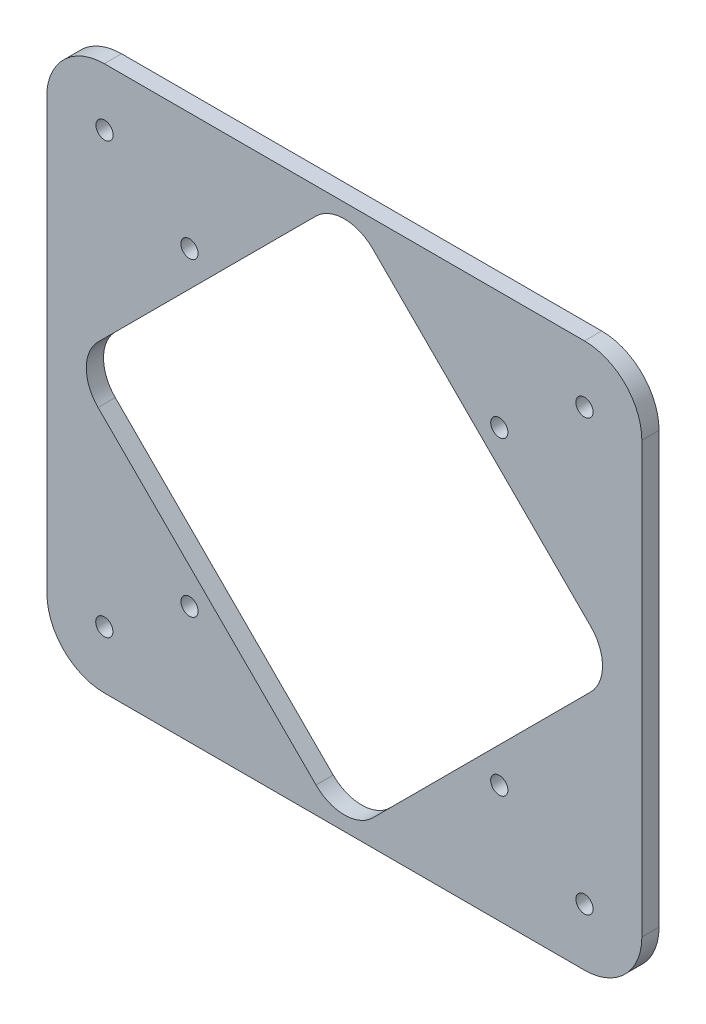
SolidWorks part; units mm, degrees
ref_plane "前基準面" through (0, 0, 0) normal (0, 0, 1) x (1, 0, 0)
ref_plane "上基準面" through (0, 0, 0) normal (0, 1, 0) x (1, 0, 0)
ref_plane "右基準面" through (0, 0, 0) normal (1, 0, 0) x (0, 0, -1)
sketch "草圖1" plane through (0, 0, 0) normal (0, 0, 1) x (1, 0, 0)
  line L0 (58.3003, 1) -> (142.0003, 1) construction
  line L1 (124.4493, 24.9081) -> (143.0914, 43.5502) construction
  line L2 (105.1, 5.5588) -> (124.4493, 24.9081) construction
  line L3 (76.5584, 72.799) -> (57.2092, 53.4497) construction
  line L4 (143.0914, 53.4497) -> (105.1, 91.4411) construction
  line L5 (95.2006, 91.4411) -> (76.5584, 72.799) construction
  line L6 (58.3003, 1) -> (142.0003, 1)
  line L7 (124.4493, 24.9081) -> (143.0914, 43.5502)
  line L8 (105.1, 5.5588) -> (124.4493, 24.9081)
  line L9 (76.5584, 72.799) -> (57.2092, 53.4497)
  line L10 (143.0914, 53.4497) -> (105.1, 91.4411)
  line L11 (95.2006, 91.4411) -> (76.5584, 72.799)
  line L12 (57.2092, 43.5502) -> (95.2006, 5.5588)
  line L13 (58.3003, 96) -> (142.0003, 96)
  line L14 (48.3003, 87) -> (48.3003, 11)
  line L15 (152.0002, 11) -> (152.0002, 86)
  arc A0 (152.0002, 86) -> (142.0003, 96) centre (142.0003, 86.0001) ccw construction
  arc A1 (142.0003, 1) -> (152.0002, 11) centre (142.0002, 11) ccw construction
  arc A2 (48.3003, 11) -> (58.3003, 1) centre (58.3004, 11.0001) ccw construction
  circle A3 centre (73.1503, 21.5) radius 1.5 construction
  circle A4 centre (58.3003, 11) radius 1.5 construction
  circle A5 centre (142.0002, 11) radius 1.5 construction
  circle A6 centre (127.1503, 21.5) radius 1.5 construction
  circle A7 centre (142.0002, 86) radius 1.5 construction
  circle A8 centre (127.1503, 75.5) radius 1.5 construction
  arc A9 (143.0914, 43.5502) -> (143.0914, 53.4497) centre (138.1417, 48.5) ccw construction
  arc A10 (95.2006, 5.5588) -> (105.1, 5.5588) centre (100.1503, 10.5086) ccw construction
  arc A11 (57.2092, 53.4497) -> (57.2092, 43.5502) centre (62.1589, 48.5) ccw construction
  arc A12 (105.1, 91.4411) -> (95.2006, 91.4411) centre (100.1503, 86.4913) ccw construction
  circle A13 centre (73.1503, 75.5) radius 1.5 construction
  circle A14 centre (58.3428, 86) radius 1.5 construction
  arc A15 (58.3003, 96) -> (48.3003, 87) centre (58.3428, 85.8972) ccw construction
  arc A16 (152.0002, 86) -> (142.0003, 96) centre (142.0003, 86.0001) ccw
  arc A17 (142.0003, 1) -> (152.0002, 11) centre (142.0002, 11) ccw
  arc A18 (48.3003, 11) -> (58.3003, 1) centre (58.3004, 11.0001) ccw
  circle A19 centre (73.1503, 21.5) radius 1.5
  circle A20 centre (58.3003, 11) radius 1.5
  circle A21 centre (142.0002, 11) radius 1.5
  circle A22 centre (127.1503, 21.5) radius 1.5
  circle A23 centre (142.0002, 86) radius 1.5
  circle A24 centre (127.1503, 75.5) radius 1.5
  arc A25 (143.0914, 43.5502) -> (143.0914, 53.4497) centre (138.1417, 48.5) ccw
  arc A26 (95.2006, 5.5588) -> (105.1, 5.5588) centre (100.1503, 10.5086) ccw
  arc A27 (57.2092, 53.4497) -> (57.2092, 43.5502) centre (62.1589, 48.5) ccw
  arc A28 (105.1, 91.4411) -> (95.2006, 91.4411) centre (100.1503, 86.4913) ccw
  circle A29 centre (73.1503, 75.5) radius 1.5
  circle A30 centre (58.3428, 86) radius 1.5
  arc A31 (58.3003, 96) -> (48.3003, 87) centre (58.3428, 85.8972) ccw
  point P0 (142.0002, 86)
extrude "填料-伸長1" add sketch "草圖1" along normal blind 3
